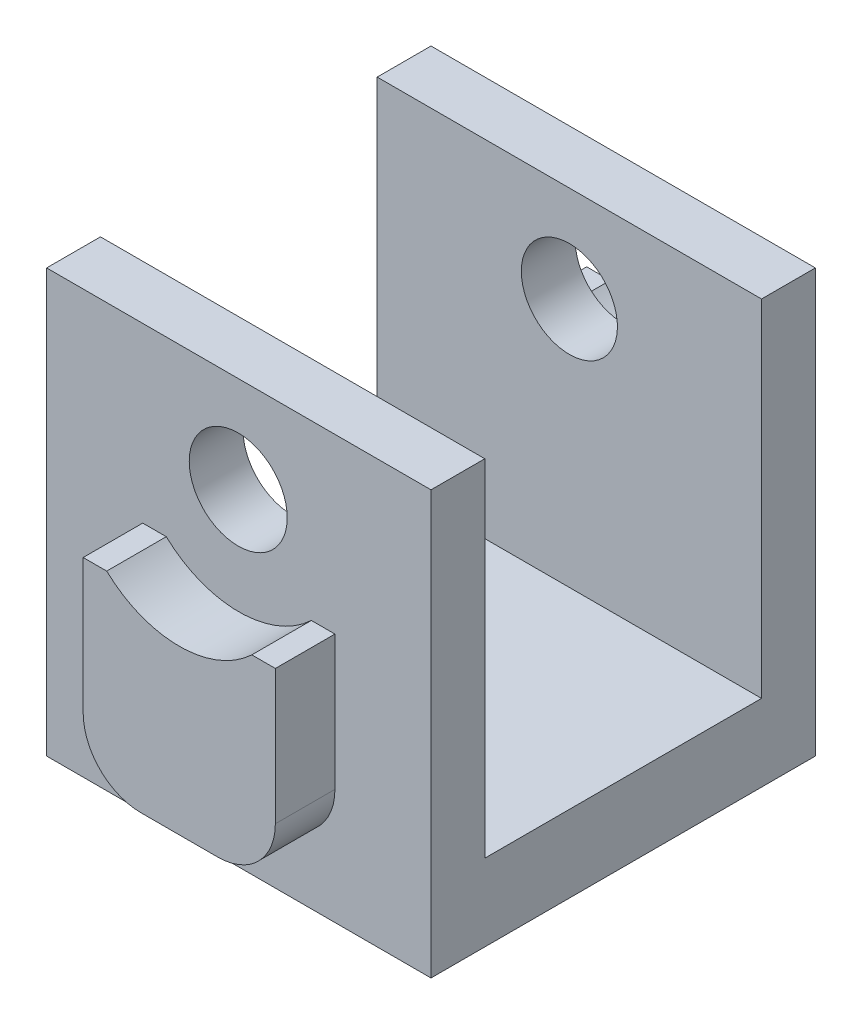
SolidWorks part; units mm, degrees
material "PLA"
ref_plane "Front Plane" through (0, 0, 0) normal (0, 0, 1) x (1, 0, 0)
ref_plane "Top Plane" through (0, 0, 0) normal (0, 1, 0) x (1, 0, 0)
ref_plane "Right Plane" through (0, 0, 0) normal (1, 0, 0) x (0, 0, -1)
ref_plane "Plane16" through (0, 32, 0) normal (0, -1, 0) x (-1, 0, 0)
ref_plane "Plane17" through (20.1, 0, 0) normal (1, 0, 0) x (0, 0, -1)
sketch "Sketch114" plane through (20.1, 0, 0) normal (1, 0, 0) x (0, 0, -1)
  line L0 (-2.9, 37) -> (-22.9, 37)
  line L1 (-22.9, 37) -> (-22.9, 15)
  line L2 (-22.9, 15) -> (-2.9, 15)
  line L3 (-2.9, 15) -> (-2.9, 37)
extrude "Boss-Extrude16" add sketch "Sketch114" against normal blind 20 separate body
sketch "Sketch115" plane through (0.1, 0, 0) normal (-1, 0, 0) x (0, 0, 1)
  line L0 (20.1, 37) -> (5.7, 37)
  line L1 (5.7, 37) -> (5.7, 19)
  line L2 (5.7, 19) -> (20.1, 19)
  line L3 (20.1, 19) -> (20.1, 37)
extrude "Cut-Extrude6" cut sketch "Sketch115" against normal through all
ref_plane "Plane18" through (0, 0, 22.9) normal (0, 0, 1) x (1, 0, 0)
sketch "Sketch121" plane through (0, 0, 22.9) normal (0, 0, 1) x (1, 0, 0)
  line L0 (5.1, 28) -> (6.3251, 28)
  line L1 (13.8749, 28) -> (15.1, 28)
  line L2 (15.1, 28) -> (15.1, 18)
  line L3 (15.1, 18) -> (5.1, 18)
  line L4 (5.1, 18) -> (5.1, 28)
  arc A0 (6.3251, 28) -> (13.8749, 28) centre (10.1, 32) ccw
extrude "Boss-Extrude17" add sketch "Sketch121" along normal blind 3.1 separate body
sketch "Sketch122" plane through (0, 0, 2.9) normal (0, 0, -1) x (-1, 0, 0)
  line L0 (-15.1, 18) -> (-15.1, 28)
  line L1 (-15.1, 28) -> (-13.8749, 28)
  line L2 (-6.3251, 28) -> (-5.1, 28)
  line L3 (-5.1, 28) -> (-5.1, 18)
  line L4 (-5.1, 18) -> (-15.1, 18)
  arc A0 (-13.8749, 28) -> (-6.3251, 28) centre (-10.1, 32) ccw
extrude "Boss-Extrude18" add sketch "Sketch122" along normal blind 3.1
hole_wizard "Ø5.0 (5) Diameter Hole1" positions "Sketch124" profile "Sketch123" hole size "Ø5.0" standard "ANSI Metric" end condition up to next
sketch "Sketch124" plane through (0, 0, 2.9) normal (0, 0, -1) x (-1, 0, 0)
  point P0 (-10.1, 32)
sketch "Sketch123" plane through (10.1, 32, 2.9) normal (1, 0, 0) x (0, 1, 0)
  line L0 (0, 0) -> (0, 2.801)
  line L1 (0, 2.801) -> (2.5, 2.801)
  line L2 (2.5, 2.801) -> (2.5, 0)
  line L5 (2.5, 0) -> (0, 0)
  line L11 (0, -6.35) -> (0, 107.95) construction
  dimension "Thru Hole Dia." = 5
  dimension "Thru Hole Depth" = 2.801
hole_wizard "CBORE for M2 Hex Head Machine Screw6" positions "Sketch126" profile "Sketch125" counterbore size "M2" standard "ANSI Metric"
sketch "Sketch126" plane through (0, 15, 0) normal (0, -1, 0) x (-1, 0, 0)
  point P0 (-10.1, -12.9)
sketch "Sketch125" plane through (10.1, 15, 12.9) normal (1, 0, 0) x (0, 0, -1)
  line L0 (0, 0) -> (0, 4)
  line L1 (0, 4) -> (1.2645, 4)
  line L2 (1.2645, 4) -> (1.2645, 1)
  line L3 (1.2645, 1) -> (3.1, 1)
  line L4 (3.1, 1) -> (3.1, 0)
  line L5 (3.1, 0) -> (0, 0)
  line L10 (0, 4) -> (-1.2645, 4) construction
  line L11 (0, -6.35) -> (0, 107.95) construction
  dimension "Hole Dia." = 2.529
  dimension "Hole Depth" = 4
  dimension "C'Bore Dia." = 6.2
  dimension "C'Bore Depth" = 1
  dimension "Drill Angle" = 180
fillet "Fillet6" radius 3 2 edges at (15.1, 18, 24.45) (5.1, 18, 24.45)
fillet "Fillet7" radius 3 2 edges at (5.1, 18, 1.35) (15.1, 18, 1.35)
hole_wizard "Ø5.1 (5.1) Diameter Hole1" positions "Sketch127" profile "Sketch128" hole size "Ø5.1" standard "ANSI Metric" end condition through all
sketch "Sketch127" plane through (0, 0, 20.1) normal (0, 0, -1) x (-1, 0, 0)
  point P0 (-10.0693, 31.998)
sketch "Sketch128" plane through (10.0693, 31.998, 20.1) normal (1, 0, 0) x (0, 1, 0)
  line L0 (0, 0) -> (0, 5.9)
  line L1 (0, 5.9) -> (2.55, 5.9)
  line L2 (2.55, 5.9) -> (2.55, 0)
  line L5 (2.55, 0) -> (0, 0)
  line L11 (0, -6.35) -> (0, 107.95) construction
  dimension "Thru Hole Dia." = 5.1
  dimension "Thru Hole Depth" = 5.9
